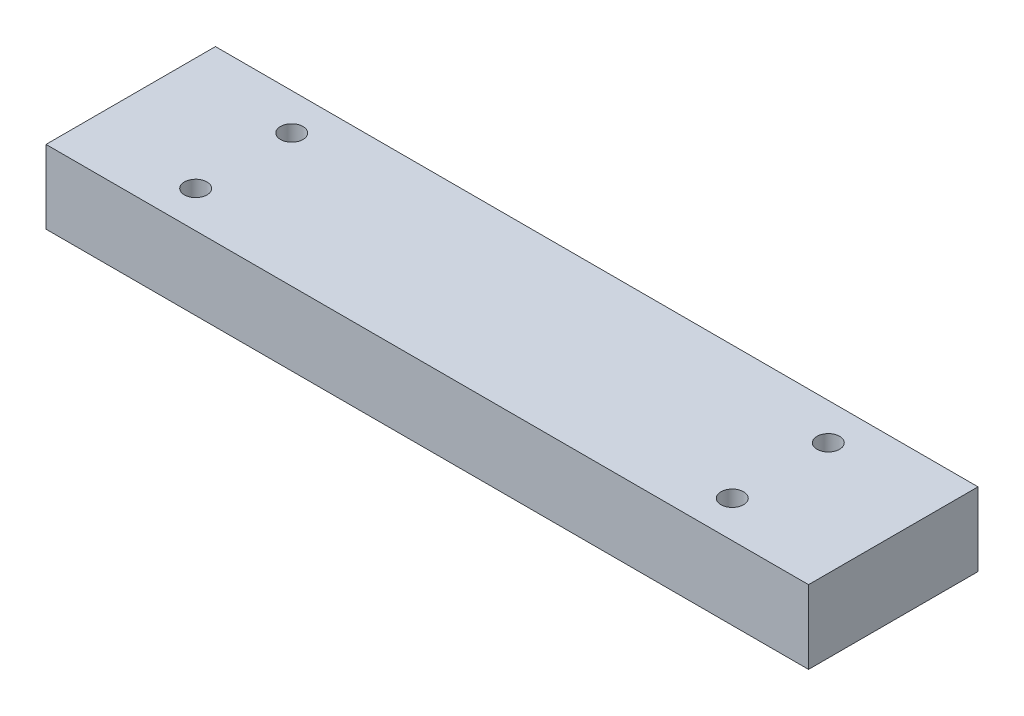
SolidWorks part; units mm, degrees
ref_plane "Front Plane" through (0, 0, 0) normal (0, 0, 1) x (1, 0, 0)
ref_plane "Top Plane" through (0, 0, 0) normal (0, 1, 0) x (1, 0, 0)
ref_plane "Right Plane" through (0, 0, 0) normal (1, 0, 0) x (0, 0, -1)
sketch "Sketch1" plane through (0, 0, 0) normal (0, 1, 0) x (1, 0, 0)
  line L1 (0, 0) -> (135, 0)
  line L2 (0, 0) -> (0, 30)
  line L3 (0, 30) -> (135, 30)
  line L4 (135, 0) -> (135, 30)
  dimension "D1" = 30
  dimension "D2" = 135
extrude "Boss-Extrude1" add sketch "Sketch1" along normal blind 13
sketch "Sketch2" plane through (0, 13, 0) normal (0, 1, 0) x (1, 0, 0)
  line L0 (0, 15) -> (20, 15) construction
  line L1 (0, 30) -> (0, 0) construction
  line L2 (135, 15) -> (115, 15) construction
  line L3 (135, 0) -> (135, 30) construction
  line L4 (115, 23.5) -> (115, 6.5)
  line L5 (20, 23.5) -> (20, 6.5)
  circle A0 centre (20, 23.5) radius 2
  circle A1 centre (20, 6.5) radius 2
  circle A2 centre (115, 23.5) radius 2
  circle A3 centre (115, 6.5) radius 2
  point P11 (115, 15)
  point P14 (20, 15)
  dimension "D3" = 4
  dimension "D1" = 20
  dimension "D2" = 17
extrude "Cut-Extrude1" cut sketch "Sketch2" against normal blind 35
